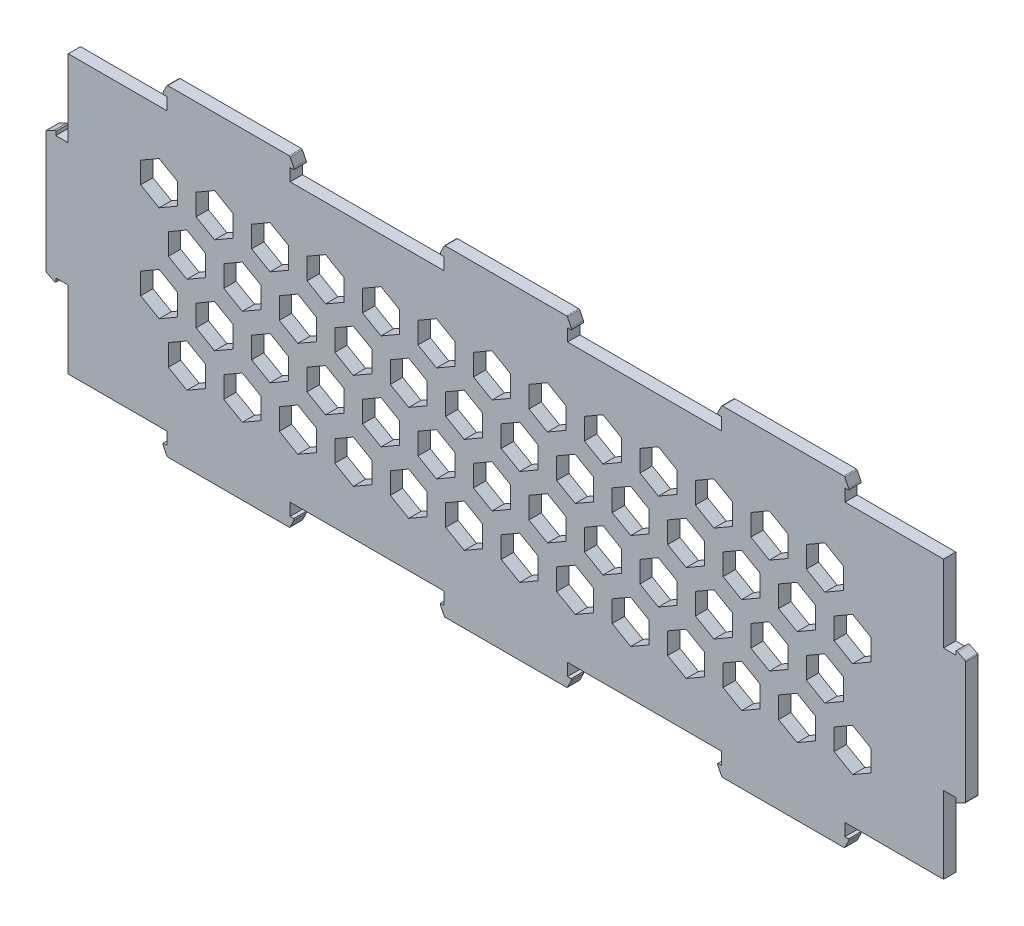
SolidWorks part; units mm, degrees
ref_plane "Front Plane" through (0, 0, 0) normal (0, 0, 1) x (1, 0, 0)
ref_plane "Top Plane" through (0, 0, 0) normal (0, 1, 0) x (1, 0, 0)
ref_plane "Right Plane" through (0, 0, 0) normal (1, 0, 0) x (0, 0, -1)
sketch "Sketch1" plane through (0, 0, 0) normal (0, 0, 1) x (1, 0, 0)
  line L0 (0, 0) -> (142, 0) construction
  line L1 (142, -22.5) -> (142, 22.5) construction
  line L2 (142, 22.5) -> (0, 22.5) construction
  line L3 (0, 22.5) -> (0, -22.5) construction
  line L8 (0, -22.5) -> (142, -22.5) construction
  line L30 (71, 22.5) -> (71, -22.5) construction
  line L31 (0, 10) -> (0, 22.5)
  line L32 (0, 22.5) -> (16, 22.5)
  line L35 (36, 22.5) -> (61, 22.5)
  line L37 (81, 22.5) -> (106, 22.5)
  line L39 (126, 22.5) -> (142, 22.5)
  line L40 (142, 22.5) -> (142, 10)
  line L42 (142, -10) -> (142, -22.5)
  line L43 (142, -22.5) -> (126, -22.5)
  line L46 (106, -22.5) -> (81, -22.5)
  line L48 (61, -22.5) -> (36, -22.5)
  line L50 (16, -22.5) -> (0, -22.5)
  line L51 (0, -22.5) -> (0, -10)
  line B0 (16, -22.5) -> (36, -22.5) construction
  line B1 (16.1618, -26.1) -> (35.8382, -26.1)
  line B2 (16, -22.5) -> (16, -24.5)
  line B3 (16, -26) -> (36, -26) construction
  line B4 (26, -26) -> (26, -22.5) construction
  line B5 (36, -22.5) -> (36, -24.5)
  line B6 (36.6, -24.8) -> (36, -26)
  line B7 (15.4, -24.8) -> (16, -26)
  line B8 (16, -24.5) -> (15.4, -24.5)
  line B9 (36, -24.5) -> (36.6, -24.5)
  arc B10 (16, -24.5) -> (15.4, -24.8) centre (15.7, -24.65) ccw construction
  arc B11 (16, -26) -> (16.1618, -26.1) centre (16.1618, -25.9191) ccw
  arc B12 (36, -26) -> (35.8382, -26.1) centre (35.8382, -25.9191) cw
  arc B13 (15.4, -24.5) -> (15.4, -24.8) centre (15.7, -24.65) ccw
  arc B14 (36.6, -24.5) -> (36.6, -24.8) centre (36.3, -24.65) cw
  line B15 (61, -22.5) -> (81, -22.5) construction
  line B16 (61.1618, -26.1) -> (80.8382, -26.1)
  line B17 (61, -22.5) -> (61, -24.5)
  line B18 (61, -26) -> (81, -26) construction
  line B19 (71, -26) -> (71, -22.5) construction
  line B20 (81, -22.5) -> (81, -24.5)
  line B21 (81.6, -24.8) -> (81, -26)
  line B22 (60.4, -24.8) -> (61, -26)
  line B23 (61, -24.5) -> (60.4, -24.5)
  line B24 (81, -24.5) -> (81.6, -24.5)
  arc B25 (61, -24.5) -> (60.4, -24.8) centre (60.7, -24.65) ccw construction
  arc B26 (61, -26) -> (61.1618, -26.1) centre (61.1618, -25.9191) ccw
  arc B27 (81, -26) -> (80.8382, -26.1) centre (80.8382, -25.9191) cw
  arc B28 (60.4, -24.5) -> (60.4, -24.8) centre (60.7, -24.65) ccw
  arc B29 (81.6, -24.5) -> (81.6, -24.8) centre (81.3, -24.65) cw
  line B30 (142, -10) -> (142, 10) construction
  line B31 (145.6, -9.8382) -> (145.6, 9.8382)
  line B32 (142, -10) -> (144, -10)
  line B33 (145.5, -10) -> (145.5, 10) construction
  line B34 (145.5, 0) -> (142, 0) construction
  line B35 (142, 10) -> (144, 10)
  line B36 (144.3, 10.6) -> (145.5, 10)
  line B37 (144.3, -10.6) -> (145.5, -10)
  line B38 (144, -10) -> (144, -10.6)
  line B39 (144, 10) -> (144, 10.6)
  arc B40 (144, -10) -> (144.3, -10.6) centre (144.15, -10.3) ccw construction
  arc B41 (145.5, -10) -> (145.6, -9.8382) centre (145.4191, -9.8382) ccw
  arc B42 (145.5, 10) -> (145.6, 9.8382) centre (145.4191, 9.8382) cw
  arc B43 (144, -10.6) -> (144.3, -10.6) centre (144.15, -10.3) ccw
  arc B44 (144, 10.6) -> (144.3, 10.6) centre (144.15, 10.3) cw
  line B45 (126, -22.5) -> (106, -22.5) construction
  line B46 (125.8382, -26.1) -> (106.1618, -26.1)
  line B47 (126, -22.5) -> (126, -24.5)
  line B48 (126, -26) -> (106, -26) construction
  line B49 (116, -26) -> (116, -22.5) construction
  line B50 (106, -22.5) -> (106, -24.5)
  line B51 (105.4, -24.8) -> (106, -26)
  line B52 (126.6, -24.8) -> (126, -26)
  line B53 (126, -24.5) -> (126.6, -24.5)
  line B54 (106, -24.5) -> (105.4, -24.5)
  arc B55 (126, -24.5) -> (126.6, -24.8) centre (126.3, -24.65) cw construction
  arc B56 (126, -26) -> (125.8382, -26.1) centre (125.8382, -25.9191) cw
  arc B57 (106, -26) -> (106.1618, -26.1) centre (106.1618, -25.9191) ccw
  arc B58 (126.6, -24.5) -> (126.6, -24.8) centre (126.3, -24.65) cw
  arc B59 (105.4, -24.5) -> (105.4, -24.8) centre (105.7, -24.65) ccw
  line B60 (16, 22.5) -> (36, 22.5) construction
  line B61 (16.1618, 26.1) -> (35.8382, 26.1)
  line B62 (16, 22.5) -> (16, 24.5)
  line B63 (16, 26) -> (36, 26) construction
  line B64 (26, 26) -> (26, 22.5) construction
  line B65 (36, 22.5) -> (36, 24.5)
  line B66 (36.6, 24.8) -> (36, 26)
  line B67 (15.4, 24.8) -> (16, 26)
  line B68 (16, 24.5) -> (15.4, 24.5)
  line B69 (36, 24.5) -> (36.6, 24.5)
  arc B70 (16, 24.5) -> (15.4, 24.8) centre (15.7, 24.65) cw construction
  arc B71 (16, 26) -> (16.1618, 26.1) centre (16.1618, 25.9191) cw
  arc B72 (36, 26) -> (35.8382, 26.1) centre (35.8382, 25.9191) ccw
  arc B73 (15.4, 24.5) -> (15.4, 24.8) centre (15.7, 24.65) cw
  arc B74 (36.6, 24.5) -> (36.6, 24.8) centre (36.3, 24.65) ccw
  line B75 (61, 22.5) -> (81, 22.5) construction
  line B76 (61.1618, 26.1) -> (80.8382, 26.1)
  line B77 (61, 22.5) -> (61, 24.5)
  line B78 (61, 26) -> (81, 26) construction
  line B79 (71, 26) -> (71, 22.5) construction
  line B80 (81, 22.5) -> (81, 24.5)
  line B81 (81.6, 24.8) -> (81, 26)
  line B82 (60.4, 24.8) -> (61, 26)
  line B83 (61, 24.5) -> (60.4, 24.5)
  line B84 (81, 24.5) -> (81.6, 24.5)
  arc B85 (61, 24.5) -> (60.4, 24.8) centre (60.7, 24.65) cw construction
  arc B86 (61, 26) -> (61.1618, 26.1) centre (61.1618, 25.9191) cw
  arc B87 (81, 26) -> (80.8382, 26.1) centre (80.8382, 25.9191) ccw
  arc B88 (60.4, 24.5) -> (60.4, 24.8) centre (60.7, 24.65) cw
  arc B89 (81.6, 24.5) -> (81.6, 24.8) centre (81.3, 24.65) ccw
  line B90 (126, 22.5) -> (106, 22.5) construction
  line B91 (125.8382, 26.1) -> (106.1618, 26.1)
  line B92 (126, 22.5) -> (126, 24.5)
  line B93 (126, 26) -> (106, 26) construction
  line B94 (116, 26) -> (116, 22.5) construction
  line B95 (106, 22.5) -> (106, 24.5)
  line B96 (105.4, 24.8) -> (106, 26)
  line B97 (126.6, 24.8) -> (126, 26)
  line B98 (126, 24.5) -> (126.6, 24.5)
  line B99 (106, 24.5) -> (105.4, 24.5)
  arc B100 (126, 24.5) -> (126.6, 24.8) centre (126.3, 24.65) ccw construction
  arc B101 (126, 26) -> (125.8382, 26.1) centre (125.8382, 25.9191) ccw
  arc B102 (106, 26) -> (106.1618, 26.1) centre (106.1618, 25.9191) cw
  arc B103 (126.6, 24.5) -> (126.6, 24.8) centre (126.3, 24.65) ccw
  arc B104 (105.4, 24.5) -> (105.4, 24.8) centre (105.7, 24.65) cw
  line B105 (0, -10) -> (0, 10) construction
  line B106 (-3.6, -9.8382) -> (-3.6, 9.8382)
  line B107 (0, -10) -> (-2, -10)
  line B108 (-3.5, -10) -> (-3.5, 10) construction
  line B109 (-3.5, 0) -> (0, 0) construction
  line B110 (0, 10) -> (-2, 10)
  line B111 (-2.3, 10.6) -> (-3.5, 10)
  line B112 (-2.3, -10.6) -> (-3.5, -10)
  line B113 (-2, -10) -> (-2, -10.6)
  line B114 (-2, 10) -> (-2, 10.6)
  arc B115 (-2, -10) -> (-2.3, -10.6) centre (-2.15, -10.3) cw construction
  arc B116 (-3.5, -10) -> (-3.6, -9.8382) centre (-3.4191, -9.8382) cw
  arc B117 (-3.5, 10) -> (-3.6, 9.8382) centre (-3.4191, 9.8382) ccw
  arc B118 (-2, -10.6) -> (-2.3, -10.6) centre (-2.15, -10.3) cw
  arc B119 (-2, 10.6) -> (-2.3, 10.6) centre (-2.15, 10.3) ccw
  dimension "D2" = 45
  dimension "D3" = 45
  dimension "D1" = 142
sketch_block_instance "insert_bloquant_20mm-2mm-1"
sketch_block "insert_bloquant_20mm-2mm" parameters "D1"=2, "D2"=1.5, "D3"=1.2, "D4"=20, "D5"=0.1, "D6"=0.6
sketch_block_instance "insert_bloquant_20mm-2mm-2"
sketch_block_instance "insert_bloquant_20mm-2mm-4"
sketch_block_instance "insert_bloquant_20mm-2mm-6"
sketch_block_instance "insert_bloquant_20mm-2mm-7"
sketch_block_instance "insert_bloquant_20mm-2mm-8"
sketch_block_instance "insert_bloquant_20mm-2mm-9"
sketch_block_instance "insert_bloquant_20mm-2mm-13"
extrude "Boss-Extrude1" add sketch "Sketch1" along normal blind 2 contours B114 B119 B111 B117 B106 B116 B112 B118 B113 B107 L51 L50 B2 B8 B13 B7 B11 B1 B12 B6 B14 B9 B5 L48 B17 B23 B28 B22 B26 B16 B27 B21 B29 B24 B20 L46 B50 B54 B59 B51 B57 B46 B56 B52 B58 B53 B47 L43 L42 B32 B38
sketch "Esquisse1" plane through (0, 0, 2) normal (0, 0, 1) x (1, 0, 0)
  line L0 (36, 22.5) -> (61, 22.5) construction
  line L1 (29.75, -5.6292) -> (31.25, 5.6292) construction
  line L2 (52.25, 5.6292) -> (53.75, -5.6292) construction
  line L3 (30.5, 0) -> (53, 0) construction
  line L4 (145.6, -9.8382) -> (145.6, 9.8382) construction
  line L5 (71, 26.1) -> (71, -26.1) construction
  line L6 (61.1618, 26.1) -> (80.8382, 26.1) construction
  line L7 (61.1618, -26.1) -> (80.8382, -26.1) construction
  line L8 (70.25, 5.6292) -> (71.75, -5.6292) construction
  point P10 (145.6, 0)
  point P18 (71, 0)
  line B0 (11.75, 9.9593) -> (14.75, 8.2272)
  line B1 (14.75, 8.2272) -> (17.75, 9.9593)
  line B2 (22.25, 5.6292) -> (19.25, 7.3612)
  line B3 (16.25, 5.6292) -> (16.25, 2.1651)
  line B4 (16.25, 2.1651) -> (19.25, 0.433)
  line B5 (19.25, 0.433) -> (22.25, 2.1651)
  line B6 (20.75, 13.4234) -> (20.75, 9.9593)
  line B7 (20.75, 9.9593) -> (23.75, 8.2272)
  line B8 (23.75, 8.2272) -> (26.75, 9.9593)
  line B9 (31.25, 5.6292) -> (28.25, 7.3612)
  line B10 (25.25, 5.6292) -> (25.25, 2.1651)
  line B11 (25.25, 2.1651) -> (28.25, 0.433)
  line B12 (28.25, 0.433) -> (31.25, 2.1651)
  line B13 (35.75, 13.4234) -> (32.75, 15.1554)
  line B14 (29.75, 13.4234) -> (29.75, 9.9593)
  line B15 (29.75, 9.9593) -> (32.75, 8.2272)
  line B16 (32.75, 8.2272) -> (35.75, 9.9593)
  line B17 (40.25, 5.6292) -> (37.25, 7.3612)
  line B18 (34.25, 5.6292) -> (34.25, 2.1651)
  line B19 (34.25, 2.1651) -> (37.25, 0.433)
  line B20 (37.25, 0.433) -> (40.25, 2.1651)
  line B21 (44.75, 13.4234) -> (41.75, 15.1554)
  line B22 (47.75, 13.4234) -> (47.75, 9.9593)
  line B23 (14.75, 15.1554) -> (11.75, 13.4234)
  line B24 (38.75, 13.4234) -> (38.75, 9.9593)
  line B25 (38.75, 9.9593) -> (41.75, 8.2272)
  line B26 (41.75, 8.2272) -> (44.75, 9.9593)
  line B27 (47.75, 9.9593) -> (50.75, 8.2272)
  line B28 (50.75, 8.2272) -> (53.75, 9.9593)
  line B29 (58.25, 5.6292) -> (55.25, 7.3612)
  line B30 (52.25, 5.6292) -> (52.25, 2.1651)
  line B31 (52.25, 2.1651) -> (55.25, 0.433)
  line B32 (55.25, 0.433) -> (58.25, 2.1651)
  line B33 (62.75, 13.4234) -> (59.75, 15.1554)
  line B34 (56.75, 13.4234) -> (56.75, 9.9593)
  line B35 (56.75, 9.9593) -> (59.75, 8.2272)
  line B36 (59.75, 8.2272) -> (62.75, 9.9593)
  line B37 (67.25, 5.6292) -> (64.25, 7.3612)
  line B38 (61.25, 5.6292) -> (61.25, 2.1651)
  line B39 (61.25, 2.1651) -> (64.25, 0.433)
  line B40 (64.25, 0.433) -> (67.25, 2.1651)
  line B41 (71.75, 13.4234) -> (68.75, 15.1554)
  line B42 (65.75, 13.4234) -> (65.75, 9.9593)
  line B43 (65.75, 9.9593) -> (68.75, 8.2272)
  line B44 (68.75, 8.2272) -> (71.75, 9.9593)
  line B45 (43.25, 2.1651) -> (46.25, 0.433)
  line B46 (46.25, 0.433) -> (49.25, 2.1651)
  line B47 (17.75, 13.4234) -> (14.75, 15.1554)
  line B48 (11.75, 13.4234) -> (11.75, 9.9593)
  line B49 (17.75, 9.9593) -> (17.75, 13.4234)
  line B50 (19.25, 7.3612) -> (16.25, 5.6292)
  line B51 (22.25, 2.1651) -> (22.25, 5.6292)
  line B52 (62.75, 9.9593) -> (62.75, 13.4234)
  line B53 (59.75, 15.1554) -> (56.75, 13.4234)
  line B54 (44.75, 9.9593) -> (44.75, 13.4234)
  line B55 (41.75, 15.1554) -> (38.75, 13.4234)
  line B56 (14.75, 11.6913) -> (71.75, 11.6913) construction
  line B57 (26.75, 9.9593) -> (26.75, 13.4234)
  line B58 (26.75, 13.4234) -> (23.75, 15.1554)
  line B59 (23.75, 15.1554) -> (20.75, 13.4234)
  line B60 (31.25, 2.1651) -> (31.25, 5.6292)
  line B61 (28.25, 7.3612) -> (25.25, 5.6292)
  line B62 (68.75, 15.1554) -> (65.75, 13.4234)
  line B63 (71.75, 9.9593) -> (71.75, 13.4234)
  line B64 (64.25, 7.3612) -> (61.25, 5.6292)
  line B65 (67.25, 2.1651) -> (67.25, 5.6292)
  line B66 (50.75, 15.1554) -> (47.75, 13.4234)
  line B67 (53.75, 13.4234) -> (50.75, 15.1554)
  line B68 (53.75, 9.9593) -> (53.75, 13.4234)
  line B69 (55.25, 7.3612) -> (52.25, 5.6292)
  line B70 (58.25, 2.1651) -> (58.25, 5.6292)
  line B71 (46.25, 7.3612) -> (43.25, 5.6292)
  line B72 (49.25, 5.6292) -> (46.25, 7.3612)
  line B73 (49.25, 2.1651) -> (49.25, 5.6292)
  line B74 (43.25, 5.6292) -> (43.25, 2.1651)
  line B75 (32.75, 15.1554) -> (29.75, 13.4234)
  line B76 (35.75, 9.9593) -> (35.75, 13.4234)
  line B77 (37.25, 7.3612) -> (34.25, 5.6292)
  line B78 (40.25, 2.1651) -> (40.25, 5.6292)
  line B79 (11.75, -5.6292) -> (14.75, -7.3612)
  line B80 (14.75, -7.3612) -> (17.75, -5.6292)
  line B81 (22.25, -9.9593) -> (19.25, -8.2272)
  line B82 (16.25, -9.9593) -> (16.25, -13.4234)
  line B83 (16.25, -13.4234) -> (19.25, -15.1554)
  line B84 (19.25, -15.1554) -> (22.25, -13.4234)
  line B85 (20.75, -2.1651) -> (20.75, -5.6292)
  line B86 (20.75, -5.6292) -> (23.75, -7.3612)
  line B87 (23.75, -7.3612) -> (26.75, -5.6292)
  line B88 (31.25, -9.9593) -> (28.25, -8.2272)
  line B89 (25.25, -9.9593) -> (25.25, -13.4234)
  line B90 (25.25, -13.4234) -> (28.25, -15.1554)
  line B91 (28.25, -15.1554) -> (31.25, -13.4234)
  line B92 (35.75, -2.1651) -> (32.75, -0.433)
  line B93 (29.75, -2.1651) -> (29.75, -5.6292)
  line B94 (29.75, -5.6292) -> (32.75, -7.3612)
  line B95 (32.75, -7.3612) -> (35.75, -5.6292)
  line B96 (40.25, -9.9593) -> (37.25, -8.2272)
  line B97 (34.25, -9.9593) -> (34.25, -13.4234)
  line B98 (34.25, -13.4234) -> (37.25, -15.1554)
  line B99 (37.25, -15.1554) -> (40.25, -13.4234)
  line B100 (44.75, -2.1651) -> (41.75, -0.433)
  line B101 (47.75, -2.1651) -> (47.75, -5.6292)
  line B102 (14.75, -0.433) -> (11.75, -2.1651)
  line B103 (38.75, -2.1651) -> (38.75, -5.6292)
  line B104 (38.75, -5.6292) -> (41.75, -7.3612)
  line B105 (41.75, -7.3612) -> (44.75, -5.6292)
  line B106 (47.75, -5.6292) -> (50.75, -7.3612)
  line B107 (50.75, -7.3612) -> (53.75, -5.6292)
  line B108 (58.25, -9.9593) -> (55.25, -8.2272)
  line B109 (52.25, -9.9593) -> (52.25, -13.4234)
  line B110 (52.25, -13.4234) -> (55.25, -15.1554)
  line B111 (55.25, -15.1554) -> (58.25, -13.4234)
  line B112 (62.75, -2.1651) -> (59.75, -0.433)
  line B113 (56.75, -2.1651) -> (56.75, -5.6292)
  line B114 (56.75, -5.6292) -> (59.75, -7.3612)
  line B115 (59.75, -7.3612) -> (62.75, -5.6292)
  line B116 (67.25, -9.9593) -> (64.25, -8.2272)
  line B117 (61.25, -9.9593) -> (61.25, -13.4234)
  line B118 (61.25, -13.4234) -> (64.25, -15.1554)
  line B119 (64.25, -15.1554) -> (67.25, -13.4234)
  line B120 (71.75, -2.1651) -> (68.75, -0.433)
  line B121 (65.75, -2.1651) -> (65.75, -5.6292)
  line B122 (65.75, -5.6292) -> (68.75, -7.3612)
  line B123 (68.75, -7.3612) -> (71.75, -5.6292)
  line B124 (43.25, -13.4234) -> (46.25, -15.1554)
  line B125 (46.25, -15.1554) -> (49.25, -13.4234)
  line B126 (17.75, -2.1651) -> (14.75, -0.433)
  line B127 (11.75, -2.1651) -> (11.75, -5.6292)
  line B128 (17.75, -5.6292) -> (17.75, -2.1651)
  line B129 (19.25, -8.2272) -> (16.25, -9.9593)
  line B130 (22.25, -13.4234) -> (22.25, -9.9593)
  line B131 (62.75, -5.6292) -> (62.75, -2.1651)
  line B132 (59.75, -0.433) -> (56.75, -2.1651)
  line B133 (44.75, -5.6292) -> (44.75, -2.1651)
  line B134 (41.75, -0.433) -> (38.75, -2.1651)
  line B135 (26.75, -5.6292) -> (26.75, -2.1651)
  line B136 (26.75, -2.1651) -> (23.75, -0.433)
  line B137 (23.75, -0.433) -> (20.75, -2.1651)
  line B138 (31.25, -13.4234) -> (31.25, -9.9593)
  line B139 (28.25, -8.2272) -> (25.25, -9.9593)
  line B140 (68.75, -0.433) -> (65.75, -2.1651)
  line B141 (71.75, -5.6292) -> (71.75, -2.1651)
  line B142 (64.25, -8.2272) -> (61.25, -9.9593)
  line B143 (67.25, -13.4234) -> (67.25, -9.9593)
  line B144 (50.75, -0.433) -> (47.75, -2.1651)
  line B145 (53.75, -2.1651) -> (50.75, -0.433)
  line B146 (53.75, -5.6292) -> (53.75, -2.1651)
  line B147 (55.25, -8.2272) -> (52.25, -9.9593)
  line B148 (58.25, -13.4234) -> (58.25, -9.9593)
  line B149 (46.25, -8.2272) -> (43.25, -9.9593)
  line B150 (49.25, -9.9593) -> (46.25, -8.2272)
  line B151 (49.25, -13.4234) -> (49.25, -9.9593)
  line B152 (43.25, -9.9593) -> (43.25, -13.4234)
  line B153 (32.75, -0.433) -> (29.75, -2.1651)
  line B154 (35.75, -5.6292) -> (35.75, -2.1651)
  line B155 (37.25, -8.2272) -> (34.25, -9.9593)
  line B156 (40.25, -13.4234) -> (40.25, -9.9593)
  line B157 (130.25, -9.9593) -> (127.25, -8.2272)
  line B158 (127.25, -8.2272) -> (124.25, -9.9593)
  line B159 (119.75, -5.6292) -> (122.75, -7.3612)
  line B160 (125.75, -5.6292) -> (125.75, -2.1651)
  line B161 (125.75, -2.1651) -> (122.75, -0.433)
  line B162 (122.75, -0.433) -> (119.75, -2.1651)
  line B163 (121.25, -13.4234) -> (121.25, -9.9593)
  line B164 (121.25, -9.9593) -> (118.25, -8.2272)
  line B165 (118.25, -8.2272) -> (115.25, -9.9593)
  line B166 (110.75, -5.6292) -> (113.75, -7.3612)
  line B167 (116.75, -5.6292) -> (116.75, -2.1651)
  line B168 (116.75, -2.1651) -> (113.75, -0.433)
  line B169 (113.75, -0.433) -> (110.75, -2.1651)
  line B170 (106.25, -13.4234) -> (109.25, -15.1554)
  line B171 (112.25, -13.4234) -> (112.25, -9.9593)
  line B172 (112.25, -9.9593) -> (109.25, -8.2272)
  line B173 (109.25, -8.2272) -> (106.25, -9.9593)
  line B174 (101.75, -5.6292) -> (104.75, -7.3612)
  line B175 (107.75, -5.6292) -> (107.75, -2.1651)
  line B176 (107.75, -2.1651) -> (104.75, -0.433)
  line B177 (104.75, -0.433) -> (101.75, -2.1651)
  line B178 (97.25, -13.4234) -> (100.25, -15.1554)
  line B179 (94.25, -13.4234) -> (94.25, -9.9593)
  line B180 (127.25, -15.1554) -> (130.25, -13.4234)
  line B181 (103.25, -13.4234) -> (103.25, -9.9593)
  line B182 (103.25, -9.9593) -> (100.25, -8.2272)
  line B183 (100.25, -8.2272) -> (97.25, -9.9593)
  line B184 (94.25, -9.9593) -> (91.25, -8.2272)
  line B185 (91.25, -8.2272) -> (88.25, -9.9593)
  line B186 (83.75, -5.6292) -> (86.75, -7.3612)
  line B187 (89.75, -5.6292) -> (89.75, -2.1651)
  line B188 (89.75, -2.1651) -> (86.75, -0.433)
  line B189 (86.75, -0.433) -> (83.75, -2.1651)
  line B190 (79.25, -13.4234) -> (82.25, -15.1554)
  line B191 (85.25, -13.4234) -> (85.25, -9.9593)
  line B192 (85.25, -9.9593) -> (82.25, -8.2272)
  line B193 (82.25, -8.2272) -> (79.25, -9.9593)
  line B194 (74.75, -5.6292) -> (77.75, -7.3612)
  line B195 (80.75, -5.6292) -> (80.75, -2.1651)
  line B196 (80.75, -2.1651) -> (77.75, -0.433)
  line B197 (77.75, -0.433) -> (74.75, -2.1651)
  line B198 (70.25, -13.4234) -> (73.25, -15.1554)
  line B199 (76.25, -13.4234) -> (76.25, -9.9593)
  line B200 (76.25, -9.9593) -> (73.25, -8.2272)
  line B201 (73.25, -8.2272) -> (70.25, -9.9593)
  line B202 (98.75, -2.1651) -> (95.75, -0.433)
  line B203 (95.75, -0.433) -> (92.75, -2.1651)
  line B204 (124.25, -13.4234) -> (127.25, -15.1554)
  line B205 (130.25, -13.4234) -> (130.25, -9.9593)
  line B206 (124.25, -9.9593) -> (124.25, -13.4234)
  line B207 (122.75, -7.3612) -> (125.75, -5.6292)
  line B208 (119.75, -2.1651) -> (119.75, -5.6292)
  line B209 (79.25, -9.9593) -> (79.25, -13.4234)
  line B210 (82.25, -15.1554) -> (85.25, -13.4234)
  line B211 (97.25, -9.9593) -> (97.25, -13.4234)
  line B212 (100.25, -15.1554) -> (103.25, -13.4234)
  line B213 (115.25, -9.9593) -> (115.25, -13.4234)
  line B214 (115.25, -13.4234) -> (118.25, -15.1554)
  line B215 (118.25, -15.1554) -> (121.25, -13.4234)
  line B216 (110.75, -2.1651) -> (110.75, -5.6292)
  line B217 (113.75, -7.3612) -> (116.75, -5.6292)
  line B218 (73.25, -15.1554) -> (76.25, -13.4234)
  line B219 (70.25, -9.9593) -> (70.25, -13.4234)
  line B220 (77.75, -7.3612) -> (80.75, -5.6292)
  line B221 (74.75, -2.1651) -> (74.75, -5.6292)
  line B222 (91.25, -15.1554) -> (94.25, -13.4234)
  line B223 (88.25, -13.4234) -> (91.25, -15.1554)
  line B224 (88.25, -9.9593) -> (88.25, -13.4234)
  line B225 (86.75, -7.3612) -> (89.75, -5.6292)
  line B226 (83.75, -2.1651) -> (83.75, -5.6292)
  line B227 (95.75, -7.3612) -> (98.75, -5.6292)
  line B228 (92.75, -5.6292) -> (95.75, -7.3612)
  line B229 (92.75, -2.1651) -> (92.75, -5.6292)
  line B230 (98.75, -5.6292) -> (98.75, -2.1651)
  line B231 (109.25, -15.1554) -> (112.25, -13.4234)
  line B232 (106.25, -9.9593) -> (106.25, -13.4234)
  line B233 (104.75, -7.3612) -> (107.75, -5.6292)
  line B234 (101.75, -2.1651) -> (101.75, -5.6292)
  line B235 (130.25, 5.6292) -> (127.25, 7.3612)
  line B236 (127.25, 7.3612) -> (124.25, 5.6292)
  line B237 (119.75, 9.9593) -> (122.75, 8.2272)
  line B238 (125.75, 9.9593) -> (125.75, 13.4234)
  line B239 (125.75, 13.4234) -> (122.75, 15.1554)
  line B240 (122.75, 15.1554) -> (119.75, 13.4234)
  line B241 (121.25, 2.1651) -> (121.25, 5.6292)
  line B242 (121.25, 5.6292) -> (118.25, 7.3612)
  line B243 (118.25, 7.3612) -> (115.25, 5.6292)
  line B244 (110.75, 9.9593) -> (113.75, 8.2272)
  line B245 (116.75, 9.9593) -> (116.75, 13.4234)
  line B246 (116.75, 13.4234) -> (113.75, 15.1554)
  line B247 (113.75, 15.1554) -> (110.75, 13.4234)
  line B248 (106.25, 2.1651) -> (109.25, 0.433)
  line B249 (112.25, 2.1651) -> (112.25, 5.6292)
  line B250 (112.25, 5.6292) -> (109.25, 7.3612)
  line B251 (109.25, 7.3612) -> (106.25, 5.6292)
  line B252 (101.75, 9.9593) -> (104.75, 8.2272)
  line B253 (107.75, 9.9593) -> (107.75, 13.4234)
  line B254 (107.75, 13.4234) -> (104.75, 15.1554)
  line B255 (104.75, 15.1554) -> (101.75, 13.4234)
  line B256 (97.25, 2.1651) -> (100.25, 0.433)
  line B257 (94.25, 2.1651) -> (94.25, 5.6292)
  line B258 (127.25, 0.433) -> (130.25, 2.1651)
  line B259 (103.25, 2.1651) -> (103.25, 5.6292)
  line B260 (103.25, 5.6292) -> (100.25, 7.3612)
  line B261 (100.25, 7.3612) -> (97.25, 5.6292)
  line B262 (94.25, 5.6292) -> (91.25, 7.3612)
  line B263 (91.25, 7.3612) -> (88.25, 5.6292)
  line B264 (83.75, 9.9593) -> (86.75, 8.2272)
  line B265 (89.75, 9.9593) -> (89.75, 13.4234)
  line B266 (89.75, 13.4234) -> (86.75, 15.1554)
  line B267 (86.75, 15.1554) -> (83.75, 13.4234)
  line B268 (79.25, 2.1651) -> (82.25, 0.433)
  line B269 (85.25, 2.1651) -> (85.25, 5.6292)
  line B270 (85.25, 5.6292) -> (82.25, 7.3612)
  line B271 (82.25, 7.3612) -> (79.25, 5.6292)
  line B272 (74.75, 9.9593) -> (77.75, 8.2272)
  line B273 (80.75, 9.9593) -> (80.75, 13.4234)
  line B274 (80.75, 13.4234) -> (77.75, 15.1554)
  line B275 (77.75, 15.1554) -> (74.75, 13.4234)
  line B276 (70.25, 2.1651) -> (73.25, 0.433)
  line B277 (76.25, 2.1651) -> (76.25, 5.6292)
  line B278 (76.25, 5.6292) -> (73.25, 7.3612)
  line B279 (73.25, 7.3612) -> (70.25, 5.6292)
  line B280 (98.75, 13.4234) -> (95.75, 15.1554)
  line B281 (95.75, 15.1554) -> (92.75, 13.4234)
  line B282 (124.25, 2.1651) -> (127.25, 0.433)
  line B283 (130.25, 2.1651) -> (130.25, 5.6292)
  line B284 (124.25, 5.6292) -> (124.25, 2.1651)
  line B285 (122.75, 8.2272) -> (125.75, 9.9593)
  line B286 (119.75, 13.4234) -> (119.75, 9.9593)
  line B287 (79.25, 5.6292) -> (79.25, 2.1651)
  line B288 (82.25, 0.433) -> (85.25, 2.1651)
  line B289 (97.25, 5.6292) -> (97.25, 2.1651)
  line B290 (100.25, 0.433) -> (103.25, 2.1651)
  line B291 (115.25, 5.6292) -> (115.25, 2.1651)
  line B292 (115.25, 2.1651) -> (118.25, 0.433)
  line B293 (118.25, 0.433) -> (121.25, 2.1651)
  line B294 (110.75, 13.4234) -> (110.75, 9.9593)
  line B295 (113.75, 8.2272) -> (116.75, 9.9593)
  line B296 (73.25, 0.433) -> (76.25, 2.1651)
  line B297 (70.25, 5.6292) -> (70.25, 2.1651)
  line B298 (77.75, 8.2272) -> (80.75, 9.9593)
  line B299 (74.75, 13.4234) -> (74.75, 9.9593)
  line B300 (91.25, 0.433) -> (94.25, 2.1651)
  line B301 (88.25, 2.1651) -> (91.25, 0.433)
  line B302 (88.25, 5.6292) -> (88.25, 2.1651)
  line B303 (86.75, 8.2272) -> (89.75, 9.9593)
  line B304 (83.75, 13.4234) -> (83.75, 9.9593)
  line B305 (95.75, 8.2272) -> (98.75, 9.9593)
  line B306 (92.75, 9.9593) -> (95.75, 8.2272)
  line B307 (92.75, 13.4234) -> (92.75, 9.9593)
  line B308 (98.75, 9.9593) -> (98.75, 13.4234)
  line B309 (109.25, 0.433) -> (112.25, 2.1651)
  line B310 (106.25, 5.6292) -> (106.25, 2.1651)
  line B311 (104.75, 8.2272) -> (107.75, 9.9593)
  line B312 (101.75, 13.4234) -> (101.75, 9.9593)
sketch_block_instance "Alveole_9mm_3mm_8x2-1"
sketch_block "Alveole_9mm_3mm_8x2" parameters "D1"=7, "D2"=1.5, "D3"=13.2857, "D4"=14
sketch_block_instance "Alveole_9mm_3mm_8x2-3"
sketch_block_instance "Alveole_9mm_3mm_8x2-4"
sketch_block_instance "Alveole_9mm_3mm_8x2-5"
extrude "Enlèv. mat.-Extru.1" cut sketch "Esquisse1" against normal through all
